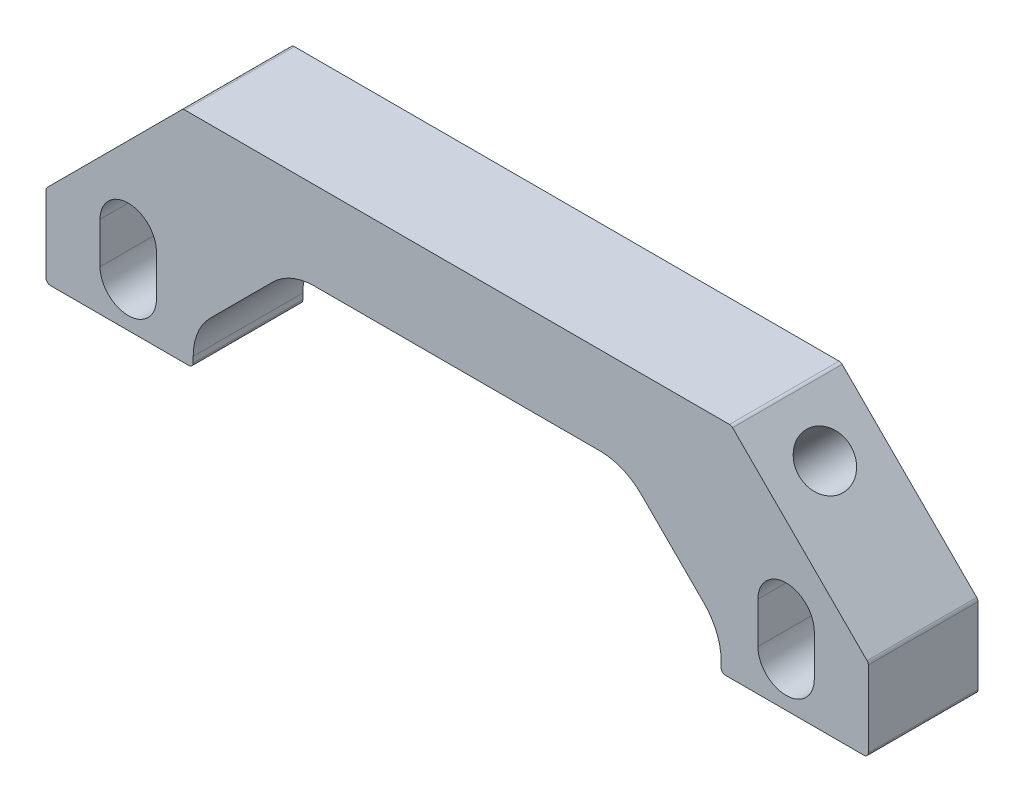
SolidWorks part; units mm, degrees
material "6061-T6 (SS)"
ref_plane "Front Plane" through (0, 0, 0) normal (0, 0, 1) x (1, 0, 0)
ref_plane "Top Plane" through (0, 0, 0) normal (0, 1, 0) x (1, 0, 0)
ref_plane "Right Plane" through (0, 0, 0) normal (1, 0, 0) x (0, 0, -1)
sketch "Sketch1" plane through (0, 0, 0) normal (0, 0, 1) x (1, 0, 0)
  line L0 (-47.625, 0) -> (47.625, 0)
  line L1 (47.625, 9.525) -> (31.75, 25.4)
  line L2 (31.75, 25.4) -> (-31.75, 25.4)
  line L3 (-31.75, 25.4) -> (-47.625, 9.525)
  line L4 (-47.625, 9.525) -> (-47.625, 0)
  line L5 (47.625, 9.525) -> (47.625, 0)
  dimension "D1" = 25.4
  dimension "D2" = 95.25
  dimension "D3" = 45
  dimension "D4" = 15.875
extrude "Boss-Extrude1" add sketch "Sketch1" along normal mid plane 12.7
sketch "Sketch2" plane through (0, 0, 6.35) normal (0, 0, 1) x (1, 0, 0)
  line L0 (-38.1, 9.525) -> (-38.1, 4.7625) construction
  line L1 (-34.8361, 9.525) -> (-34.8361, 4.7625)
  line L2 (-41.3639, 9.525) -> (-41.3639, 4.7625)
  line L3 (38.1, 9.525) -> (38.1, 4.7625) construction
  line L4 (41.3639, 9.525) -> (41.3639, 4.7625)
  line L5 (34.8361, 9.525) -> (34.8361, 4.7625)
  line L6 (-38.1, 7.1438) -> (0, 0) construction
  line L7 (0, 0) -> (38.1, 7.1438) construction
  line L8 (-47.625, 0) -> (47.625, 0) construction
  arc A0 (-34.8361, 9.525) -> (-41.3639, 9.525) centre (-38.1, 9.525) ccw
  arc A1 (-41.3639, 4.7625) -> (-34.8361, 4.7625) centre (-38.1, 4.7625) ccw
  arc A2 (41.3639, 9.525) -> (34.8361, 9.525) centre (38.1, 9.525) ccw
  arc A3 (34.8361, 4.7625) -> (41.3639, 4.7625) centre (38.1, 4.7625) ccw
  point P2 (-38.1, 7.1438)
  point P8 (38.1, 7.1438)
  dimension "D1" = 6.5278
  dimension "D2" = 76.2
  dimension "D3" = 4.7625
  dimension "D4" = 4.7625
extrude "Cut-Extrude1" cut sketch "Sketch2" against normal through all
sketch "Sketch3" plane through (0, 0, 6.35) normal (0, 0, 1) x (1, 0, 0)
  line L0 (-41.9045, 26.5742) -> (35313.4346, -35328.7648) construction
  line L1 (-31.75, 25.4) -> (-47.625, 9.525) construction
  line L2 (-30.5744, 4.0189) -> (-19.3491, 15.2442)
  line L4 (-19.3491, 15.2442) -> (19.3491, 15.2442)
  line L5 (19.3491, 15.2442) -> (30.5744, 4.0189)
  line L6 (30.5744, 0) -> (-30.5744, 0)
  line L7 (-30.5744, 4.0189) -> (-30.5744, 0)
  line L8 (30.5744, 4.0189) -> (30.5744, 0)
  point P4 (0, 0)
  point P7 (-24.9618, 9.6315)
  point P16 (20.6233, 13.3084)
  dimension "D4" = 15.95
  dimension "D1" = 45
  dimension "D2" = 15.875
  dimension "D3" = 6.35
extrude "Cut-Extrude2" cut sketch "Sketch3" against normal through all
fillet "Fillet1" radius 6.858 4 edges at (30.5744, 4.0189, 0) (19.3491, 15.2442, 0) (-30.5744, 4.0189, 0) (-19.3491, 15.2442, 0)
hole_wizard "Ø6.0mm Clearance Dowel Hole1" positions "Sketch5" profile "Sketch6" hole size "Ø6.0" standard "ANSI Metric" end condition through all
sketch "Sketch5" plane through (-17.2966, 17.2966, 0) normal (0.7071, -0.7071, 0) x (-0.7071, -0.7071, 0)
  line L0 (4.4901, -6.35) -> (4.4901, 6.35) construction
  point P0 (10.8401, 0)
  dimension "D1" = 6.35
sketch "Sketch6" plane through (-24.9618, 9.6315, 0) normal (0, 0, 1) x (0.7071, 0.7071, 0)
  line L0 (0, 0) -> (0, 27.1753)
  line L1 (0, 27.1753) -> (3, 27.1753)
  line L2 (3, 27.1753) -> (3, 0)
  line L5 (3, 0) -> (0, 0)
  line L11 (0, -6.35) -> (0, 107.95) construction
  dimension "Thru Hole Dia." = 6
  dimension "Thru Hole Depth" = 27.1753
mirror "Mirror2" about plane through (0, 0, 0) normal (1, 0, 0) of "Ø6.0mm Clearance Dowel Hole1"
fillet "Fillet2" radius 0.508 8 edges at (-31.75, 25.4, 0) (-47.625, 9.525, 0) (-47.625, 0, 0) (-30.5744, 0, 0) (30.5744, 0, 0) (47.625, 0, 0) (47.625, 9.525, 0) (31.75, 25.4, 0)
